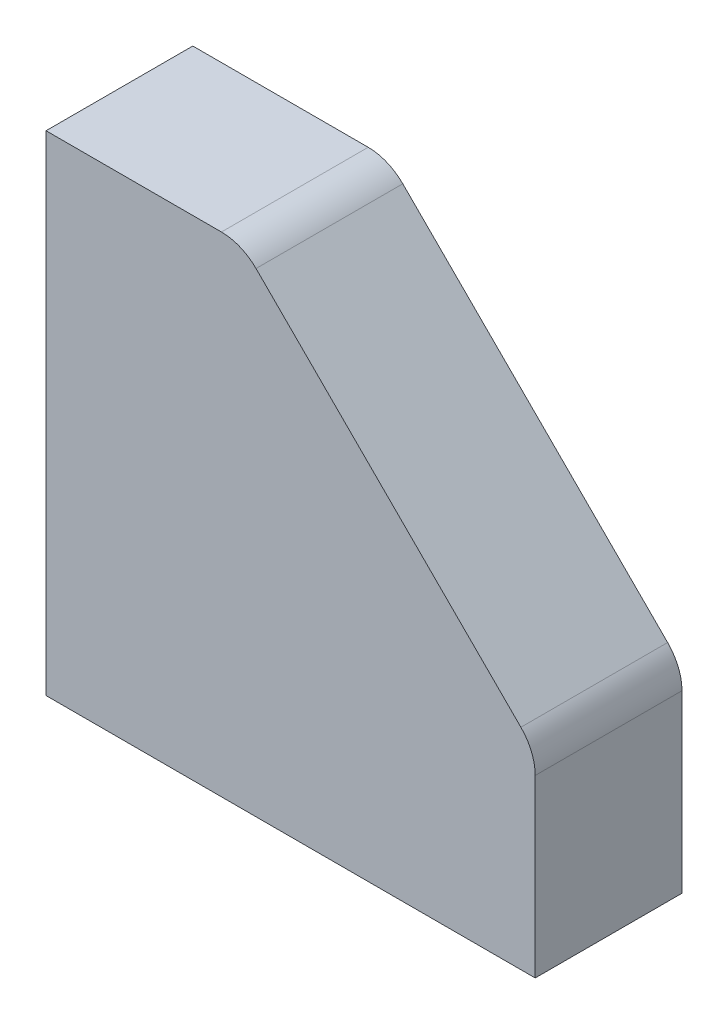
SolidWorks part; units mm, degrees
material "6061-T6 (SS)"
ref_plane "Front Plane" through (0, 0, 0) normal (0, 0, 1) x (1, 0, 0)
ref_plane "Top Plane" through (0, 0, 0) normal (0, 1, 0) x (1, 0, 0)
ref_plane "Right Plane" through (0, 0, 0) normal (1, 0, 0) x (0, 0, -1)
sketch "Sketch1" plane through (0, 0, 0) normal (0, 0, 1) x (1, 0, 0)
  line L0 (0, 0) -> (21.397, 0) construction
  line L1 (21.397, 0) -> (0, 0) construction
  line L2 (0, 0) -> (0, 13.9546) construction
  line L3 (0, 50) -> (20, 50)
  line L4 (20, 50) -> (50, 20)
  line L5 (50, 20) -> (50, 0)
  line L6 (50, 0) -> (0, 0)
  line L7 (0, 0) -> (0, 50)
  dimension "D1" = 50
  dimension "D2" = 20
  dimension "D3" = 20
  dimension "D4" = 50
extrude "Boss-Extrude1" add sketch "Sketch1" along normal blind 15
sketch "Sketch2" plane through (0, 0, 0) normal (-1, 0, 0) x (0, 0, 1)
  line L0 (7.5, 50) -> (7.5, 0) construction
  line L1 (15, 50) -> (0, 50) construction
  line L2 (15, 0) -> (0, 0) construction
  line L3 (0, 15) -> (15, 15) construction
  line L4 (0, 50) -> (0, 0) construction
  line L5 (15, 50) -> (15, 0) construction
  line L6 (0, 40) -> (15, 40) construction
  circle A0 centre (7.5, 40) radius 4.179 construction
  circle A1 centre (7.5, 15) radius 4.1533 construction
  dimension "D1" = 25
  dimension "D2" = 15
hole_wizard "M4 Tapped Hole1" positions "3DSketch1" profile "Sketch3" tap size "M4" standard "ISO"
sketch3d "3DSketch1"
  point P0 (0, 40, 7.5)
  point P3 (0, 15, 7.5)
sketch "Sketch3" plane through (0, 40, 7.5) normal (0, 1, 0) x (0, 0, 1)
  line L0 (0, 0) -> (0, 10.1)
  line L1 (0, 10.1) -> (1.65, 9.1086)
  line L2 (1.65, 9.1086) -> (1.65, 0)
  line L5 (1.65, 0) -> (0, 0)
  line L10 (0, 10.1) -> (-1.65, 9.1086) construction
  line L11 (0, -6.35) -> (0, 107.95) construction
  dimension "Tap Drill Dia." = 3.3
  dimension "Tap Drill Depth" = 10.1
  dimension "Drill Angle" = 118
cosmetic thread "Hole Thread1" parameters "D1"=8, "D2"=4
cosmetic thread "Hole Thread2" parameters "D1"=8, "D2"=4
sketch "Sketch4" plane through (0, 0, 0) normal (0, -1, 0) x (1, 0, 0)
  line L0 (5, 15) -> (5, 0) construction
  line L1 (0, 15) -> (50, 15) construction
  line L2 (0, 0) -> (50, 0) construction
  line L3 (20, 15) -> (20, 0) construction
  line L4 (35, 15) -> (35, 0) construction
  line L5 (0, 7.5) -> (50, 7.5) construction
  line L6 (0, 11.679) -> (0, 3.321) construction
  line L7 (50, 15) -> (50, 0) construction
  circle A0 centre (5, 7.5) radius 3.7049 construction
  circle A1 centre (20, 7.5) radius 4.0819 construction
  circle A2 centre (35, 7.5) radius 3.56 construction
  dimension "D1" = 15
  dimension "D2" = 15
  dimension "D3" = 15
hole_wizard "M4 Tapped Hole2" positions "Sketch5" profile "Sketch6" tap size "M4" standard "ISO"
sketch "Sketch5" plane through (0, 0, 0) normal (0, -1, 0) x (-1, 0, 0)
  point P0 (-35, -7.5)
  point P3 (-20, -7.5)
  point P6 (-5, -7.5)
sketch "Sketch6" plane through (35, 0, 7.5) normal (1, 0, 0) x (0, 0, -1)
  line L0 (0, 0) -> (0, 10.1)
  line L1 (0, 10.1) -> (1.65, 9.1086)
  line L2 (1.65, 9.1086) -> (1.65, 0)
  line L5 (1.65, 0) -> (0, 0)
  line L10 (0, 10.1) -> (-1.65, 9.1086) construction
  line L11 (0, -6.35) -> (0, 107.95) construction
  dimension "Tap Drill Dia." = 3.3
  dimension "Tap Drill Depth" = 10.1
  dimension "Drill Angle" = 118
cosmetic thread "Hole Thread3" parameters "D1"=8, "D2"=4
cosmetic thread "Hole Thread4" parameters "D1"=8, "D2"=4
cosmetic thread "Hole Thread5" parameters "D1"=8, "D2"=4
fillet "Fillet1" radius 5 2 edges at (50, 20, 7.5) (20, 50, 7.5)
